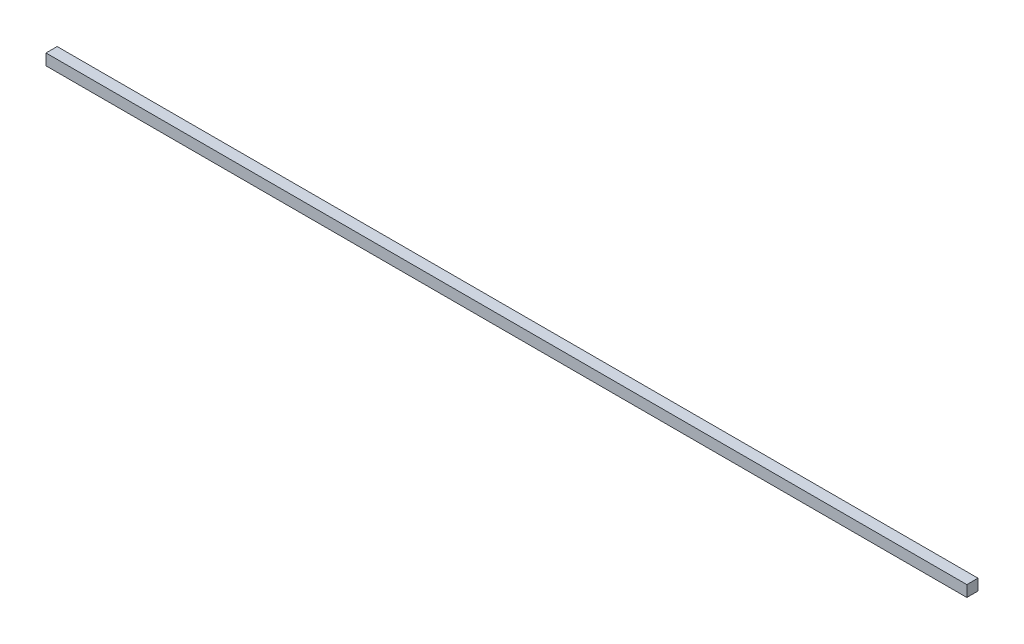
SolidWorks part; units mm, degrees
ref_plane "Front Plane" through (0, 0, 0) normal (0, 0, 1) x (1, 0, 0)
ref_plane "Top Plane" through (0, 0, 0) normal (0, 1, 0) x (1, 0, 0)
ref_plane "Right Plane" through (0, 0, 0) normal (1, 0, 0) x (0, 0, -1)
other "Configuration Table"
sketch "Sketch1" plane through (0, 0, 0) normal (0, 0, 1) x (1, 0, 0)
  line L1 (20, 202) -> (680, 202)
  line L2 (20, 202) -> (20, 210)
  line L3 (20, 210) -> (680, 210)
  line L4 (680, 202) -> (680, 210)
extrude "TOPPING_klape_alt2_pivot_mil_1" add sketch "Sketch1" along normal blind 8 from offset 22 separate body
